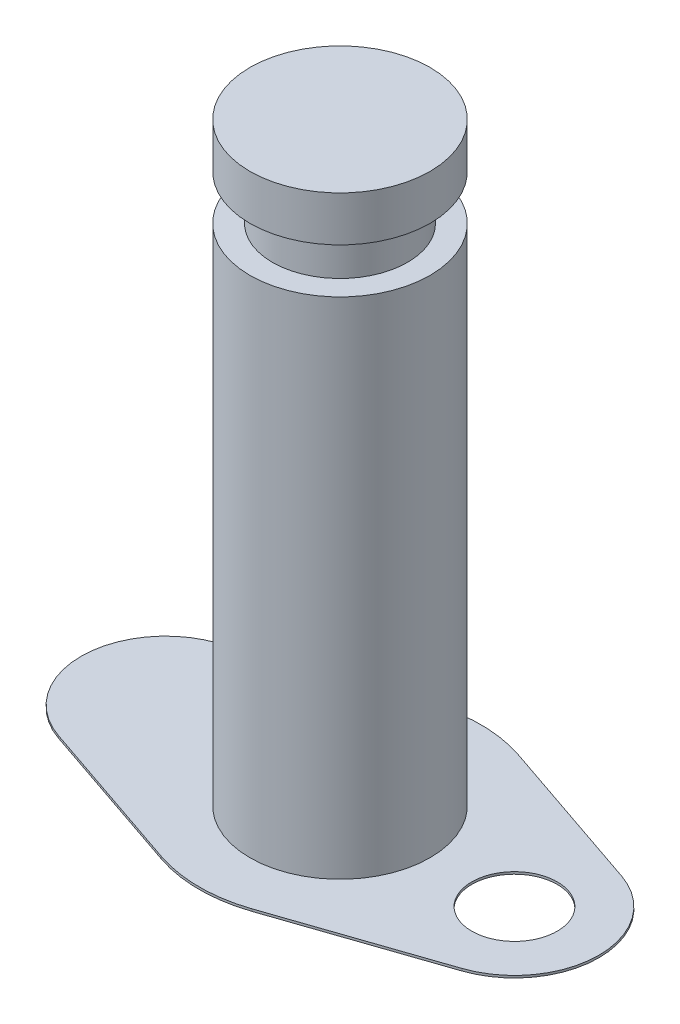
SolidWorks part; units mm, degrees
ref_plane "Front Plane" through (0, 0, 0) normal (0, 0, 1) x (1, 0, 0)
ref_plane "Top Plane" through (0, 0, 0) normal (0, 1, 0) x (1, 0, 0)
ref_plane "Right Plane" through (0, 0, 0) normal (1, 0, 0) x (0, 0, -1)
sketch "Sketch1" plane through (0, 0, 0) normal (0, 1, 0) x (1, 0, 0)
  line L0 (-8.9597, 3.5495) -> (-2.0161, 5.9159)
  line L1 (-8.9597, -3.5495) -> (-2.0161, -5.9159)
  line L2 (2.0161, 5.9159) -> (8.9597, 3.5495)
  line L3 (8.9597, -3.5495) -> (2.0161, -5.9159)
  circle A0 centre (0, 0) radius 4 construction
  circle A1 centre (0, 0) radius 6.25
  circle A2 centre (7.75, 0) radius 2.5 construction
  circle A3 centre (-7.75, 0) radius 2.5 construction
  circle A4 centre (-7.75, 0) radius 3.75
  circle A5 centre (7.75, 0) radius 3.75
  dimension "D1" = 7.5
  dimension "D2" = 8
  dimension "D3" = 12.5
  dimension "D4" = 5
extrude "Boss-Extrude1" add sketch "Sketch1" along normal blind 0.1 contours A1 A4 A3 | A1 A4 A3 | A5 A1 A4 | A4 L1 A1 | A5 A1 L3 | A1 A5 A2 | A5 A1 A2 | A5 L2 A1 | A4 A1 L0
sketch "Sketch2" plane through (0, 0, 0) normal (0, 1, 0) x (1, 0, 0)
  line L0 (0, -6.25) -> (0, 6.25) construction
  line L1 (11.5, 0) -> (-11.5, 0) construction
  arc A0 (-2.0161, -5.9159) -> (2.0161, -5.9159) centre (0, 0) ccw construction
  arc A1 (2.0161, 5.9159) -> (-2.0161, 5.9159) centre (0, 0) ccw construction
  arc A2 (8.9597, -3.5495) -> (8.9597, 3.5495) centre (7.75, 0) ccw construction
  arc A3 (-8.9597, 3.5495) -> (-8.9597, -3.5495) centre (-7.75, 0) ccw construction
  circle A4 centre (0, 0) radius 4
extrude "Boss-Extrude2" add sketch "Sketch2" along normal blind 22.5
sketch "Sketch3" plane through (0, 22.5, 0) normal (0, 1, 0) x (1, 0, 0)
  circle A0 centre (0, 0) radius 3
  dimension "D1" = 6
extrude "Boss-Extrude3" add sketch "Sketch3" along normal blind 2
sketch "Sketch4" plane through (0, 24.5, 0) normal (0, 1, 0) x (1, 0, 0)
  circle A0 centre (0, 0) radius 4
extrude "Boss-Extrude4" add sketch "Sketch4" along normal blind 2
hole_wizard "#6 Clearance Hole1" positions "Sketch5" profile "Sketch6" hole size "#6" standard "ANSI Inch"
sketch "Sketch5" plane through (0, 0.1, 0) normal (0, 1, 0) x (1, 0, 0)
  point P3 (7.75, 0)
  point P6 (0, 0)
sketch "Sketch6" plane through (7.75, 0.1, 0) normal (1, 0, 0) x (0, 0, 1)
  line L0 (0, 0) -> (0, 0.1)
  line L1 (0, 0.1) -> (1.8986, 0.1)
  line L2 (1.8986, 0.1) -> (1.8986, 0)
  line L5 (1.8986, 0) -> (0, 0)
  line L11 (0, -6.35) -> (0, 107.95) construction
  dimension "Thru Hole Dia." = 3.7973
  dimension "Thru Hole Depth" = 0.1
hole_wizard "#6-32 Tapped Hole2" positions "Sketch9" profile "Sketch10" tap size "#6-32" standard "ANSI Inch"
sketch "Sketch9" plane through (0, 0.1, 0) normal (0, -1, 0) x (-1, 0, 0)
  point P0 (0, 0)
sketch "Sketch10" plane through (0, 0.1, 0) normal (1, 0, 0) x (0, 0, -1)
  line L0 (0, 0) -> (0, 10.2027)
  line L1 (0, 10.2027) -> (1.3525, 9.39)
  line L2 (1.3525, 9.39) -> (1.3525, 0)
  line L5 (1.3525, 0) -> (0, 0)
  line L10 (0, 10.2027) -> (-1.3526, 9.39) construction
  line L11 (0, -6.35) -> (0, 107.95) construction
  dimension "Tap Drill Dia." = 2.7051
  dimension "Tap Drill Depth" = 9.39
  dimension "Drill Angle" = 118
cosmetic thread "Hole Thread2" parameters "D1"=7.01, "D2"=3.5052
